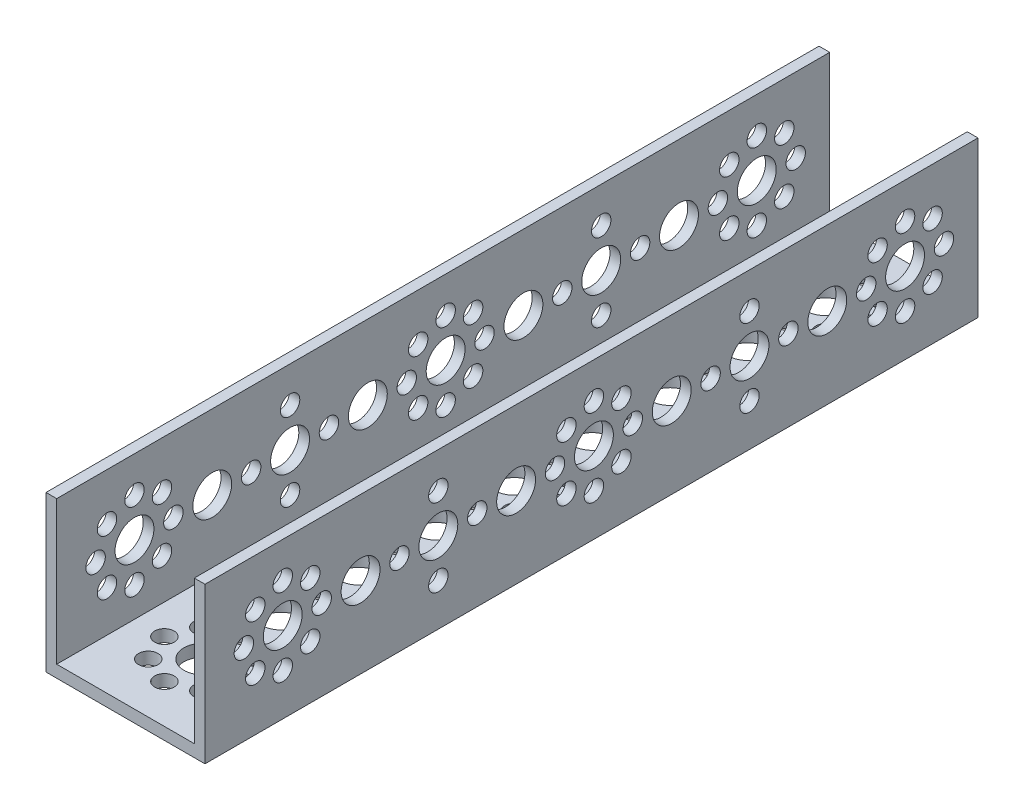
SolidWorks part; units mm, degrees
ref_plane "Front Plane" through (0, 0, 0) normal (0, 0, 1) x (1, 0, 0)
ref_plane "Top Plane" through (0, 0, 0) normal (0, 1, 0) x (1, 0, 0)
ref_plane "Right Plane" through (0, 0, 0) normal (1, 0, 0) x (0, 0, -1)
sketch "Esquisse1" plane through (0, 0, 0) normal (0, 0, 1) x (1, 0, 0)
  line L0 (0, 0) -> (0, 32)
  line L1 (0, 32) -> (2.2, 32)
  line L2 (2.2, 32) -> (2.2, 2.5)
  line L3 (2.2, 2.5) -> (30.5, 2.5)
  line L4 (30.5, 2.5) -> (30.5, 32)
  line L5 (30.5, 32) -> (32.7, 32)
  line L6 (32.7, 32) -> (32.7, 0)
  line L7 (32.7, 0) -> (0, 0)
  dimension "D1" = 32
  dimension "D2" = 2.2
  dimension "D3" = 2.2
  dimension "D4" = 2.5
  dimension "D5" = 32
  dimension "D6" = 32.7
  dimension "D7" = 28.3
extrude "Boss.-Extru.1" add sketch "Esquisse1" along normal blind 159
ref_plane "Plan1" through (0, 0, 0) normal (0, -1, 0) x (-1, 0, 0)
sketch "Esquisse2" plane through (0, 0, 0) normal (0, -1, 0) x (-1, 0, 0)
  line L0 (0, -159) -> (-32.7, -159) construction
  line L1 (-32.7, -159) -> (-32.7, 0) construction
  circle A0 centre (-16.35, -143) radius 4
  point P4 (-16.35, -159)
  dimension "D1" = 8
  dimension "D2" = 16
  dimension "D3" = 16.35
extrude "Enlèv. mat.-Extru.1" cut sketch "Esquisse2" against normal through all both and the other way through all
pattern_linear "Répétition linéaire1" count 9 spacing 16 along (0, 0, -1) of "Enlèv. mat.-Extru.1"
sketch "Esquisse3" plane through (0, 0, 0) normal (0, -1, 0) x (1, 0, 0)
  circle A0 centre (24.35, 143) radius 2
  circle A1 centre (16.35, 143) radius 4 construction
  dimension "D1" = 4
  dimension "D2" = 8
  dimension "D3" = 0
extrude "Enlèv. mat.-Extru.2" cut sketch "Esquisse3" against normal through all both and the other way through all contours A0
pattern_circular "Répétition circulaire1" count 4 over 360 about axis through (16.35, 0, 143) along (0, 1, 0) of "Enlèv. mat.-Extru.2"
pattern_circular "Répétition circulaire2" count 8 over 360 about axis through (16.35, 0, 143) along (0, 1, 0) skipping 2, 4, 6 of "Enlèv. mat.-Extru.2"
pattern_linear "Répétition linéaire2" count 10 spacing 16 along (0, 0, -1) skipping (1, 0), (3, 0), (5, 0), (7, 0), (9, 0) of "Répétition circulaire1", "Enlèv. mat.-Extru.2"
pattern_linear "Répétition linéaire3" count 9 spacing 16 along (0, 0, -1) skipping (1, 0), (2, 0), (3, 0), (5, 0), (6, 0), (7, 0) of "Répétition circulaire2"
ref_plane "Plan4" through (30.5, 0, 0) normal (-1, 0, 0) x (0, 0, 1)
ref_point "Point2" parameters "D1"=28.3
ref_plane "Plan5" through (-0.15, 0.15, 0) normal (0.7071, -0.7071, 0) x (0, 0, -1)
mirror "Symétrie2" about plane through (-0.15, 0.15, 0) normal (0.7071, -0.7071, 0) of "Répétition linéaire3", "Répétition linéaire2", "Répétition circulaire2", "Répétition circulaire1", "Enlèv. mat.-Extru.2", "Répétition linéaire1", "Enlèv. mat.-Extru.1"
